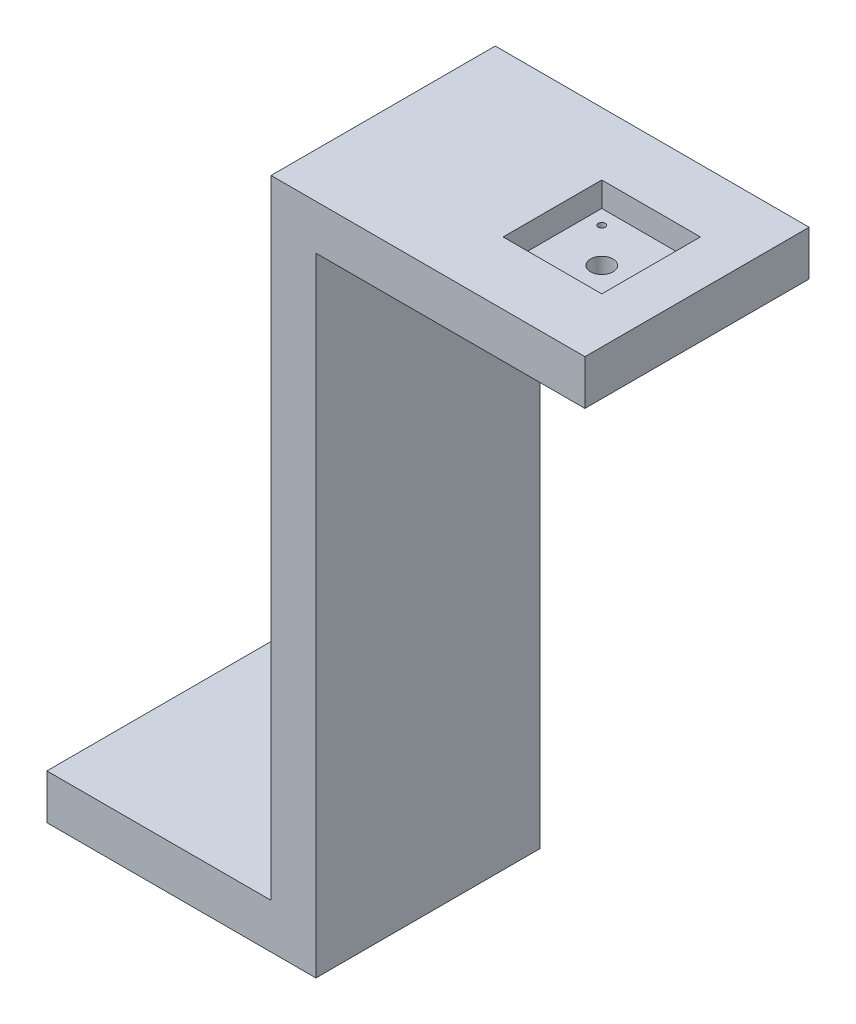
SolidWorks part; units mm, degrees
ref_plane "Front Plane" through (0, 0, 0) normal (0, 0, 1) x (1, 0, 0)
ref_plane "Top Plane" through (0, 0, 0) normal (0, 1, 0) x (1, 0, 0)
ref_plane "Right Plane" through (0, 0, 0) normal (1, 0, 0) x (0, 0, -1)
sketch "Sketch1" plane through (0, 0, 0) normal (0, 0, 1) x (1, 0, 0)
  line L10 (0, 0) -> (0, 280)
  line L11 (0, 280) -> (120, 280)
  line L12 (120, 280) -> (120, 300)
  line L13 (120, 300) -> (-20, 300)
  line L14 (-20, 300) -> (-20, 20)
  line L15 (-20, 20) -> (-120, 20)
  line L16 (-120, 20) -> (-120, 0)
  line L17 (55, 0) -> (-55, 0) construction
  line L18 (-120, 0) -> (0, 0)
extrude "Boss-Extrude1" add sketch "Sketch1" along normal blind 100
sketch "Sketch2" plane through (0, 300, 0) normal (0, 1, 0) x (1, 0, 0)
  line L0 (-132, 0) -> (132, 0) construction
  line L1 (-20, 0) -> (120, 0)
  line L2 (-20, 0) -> (-20, -100)
  line L3 (-20, -100) -> (120, -100)
  line L4 (120, 0) -> (120, -100)
  line L5 (-20, -100) -> (-20, 0) construction
  line L6 (100, -50) -> (120, -50)
  line L7 (55, -72.5) -> (100, -72.5)
  line L8 (55, -72.5) -> (55, -27.5)
  line L9 (55, -27.5) -> (100, -27.5)
  line L10 (100, -72.5) -> (100, -27.5)
  line L11 (55, -72.5) -> (100, -27.5) construction
  line L12 (55, -27.5) -> (100, -72.5) construction
  circle A0 centre (77.5, -50) radius 5
extrude "Cut-Extrude1" cut sketch "Sketch2" against normal blind 100 contours A0
sketch "Sketch6" plane through (0, 300, 0) normal (0, 1, 0) x (1, 0, 0)
  line L1 (55.5, -28) -> (99.5, -28)
  line L2 (55.5, -28) -> (55.5, -72)
  line L3 (55.5, -72) -> (99.5, -72)
  line L4 (99.5, -28) -> (99.5, -72)
  line L5 (55.5, -28) -> (99.5, -72) construction
  line L6 (55.5, -72) -> (99.5, -28) construction
  point P0 (77.5, -50)
extrude "Cut-Extrude2" cut sketch "Sketch6" against normal blind 11
sketch "Sketch7" plane through (0, 289, 0) normal (0, 1, 0) x (1, 0, 0)
  line L0 (77.5, -50) -> (77.5, -34.5)
  line L1 (77.5, -34.5) -> (93, -34.5)
  line L2 (93, -34.5) -> (93, -65.5)
  line L3 (93, -65.5) -> (62, -65.5)
  line L4 (62, -65.5) -> (62, -34.5)
  circle A0 centre (62, -34.5) radius 1.55
  circle A1 centre (93, -34.5) radius 1.55
  circle A2 centre (93, -65.5) radius 1.55
  circle A3 centre (62, -65.5) radius 1.55
extrude "Cut-Extrude3" cut sketch "Sketch7" against normal blind 11
